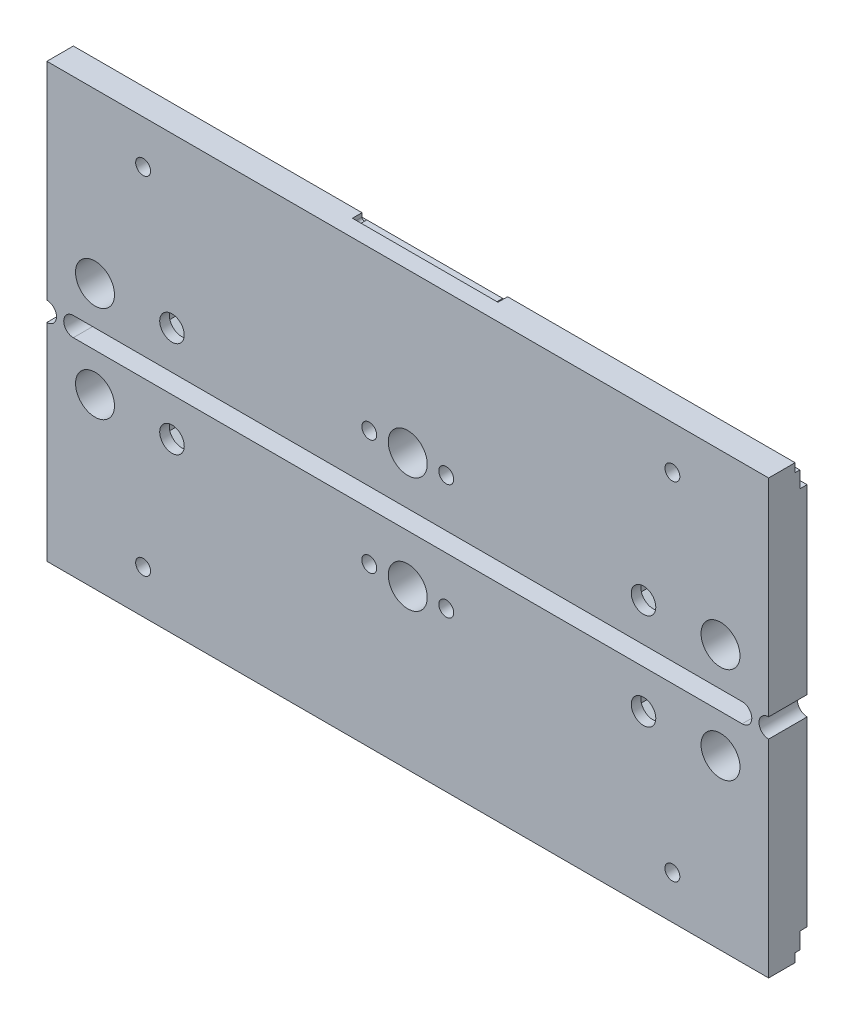
SolidWorks part; units mm, degrees
ref_plane "前视基准面" through (0, 0, 0) normal (0, 0, 1) x (1, 0, 0)
ref_plane "上视基准面" through (0, 0, 0) normal (0, 1, 0) x (1, 0, 0)
ref_plane "右视基准面" through (0, 0, 0) normal (1, 0, 0) x (0, 0, -1)
sketch "前视图草图" plane through (0, 0, 0) normal (0, 0, 1) x (1, 0, 0)
  line L0 (0, 0) -> (8.5179, 0) construction
  line L1 (0, 0) -> (0, 5.4227) construction
sketch "草图2" plane through (0, 0, 0) normal (0, 0, 1) x (1, 0, 0)
  line L0 (0, 0) -> (150, 0)
  line L1 (-200000, 0) -> (200008.5179, 0) construction
  line L2 (150, 0) -> (150, 43)
  line L3 (150, 43) -> (0, 43)
  line L4 (0, -200000) -> (0, 200005.4227) construction
  line L5 (0, 43) -> (0, 0)
  line L6 (75, 43) -> (75, 0) construction
  circle A0 centre (10, 8) radius 4.05
  circle A1 centre (75, 10) radius 4.05
  circle A2 centre (140, 8) radius 4.05
  dimension "D3" = 8
  dimension "D5" = 10
  dimension "D9" = 8.1
  dimension "D10" = 8.1
  dimension "D11" = 8.1
  dimension "D1" = 43
  dimension "D2" = 150
  dimension "D4" = 65
  dimension "D6" = 65
  dimension "D7" = 8
extrude "凸台-拉伸1" add sketch "草图2" along normal blind 8
sketch "草图3" plane through (0, 0, 8) normal (0, 0, 1) x (1, 0, 0)
  line L0 (19.088, 8) -> (34.4805, 8) construction
  line L1 (10, 8) -> (10, 16.8386) construction
  line L2 (140, 8) -> (140, 16.5917) construction
  circle A0 centre (10, 8) radius 4.05 construction
  circle A2 centre (26, 8) radius 2.55
  circle A3 centre (124, 8) radius 2.55
  circle A4 centre (10, 8) radius 4.05 construction
  point P9 (0, 0)
  dimension "D4" = 5.1
  dimension "D5" = 5.1
  dimension "D2" = 16
  dimension "D3" = 16
extrude "切除-拉伸1" cut sketch "草图3" against normal through all
sketch "草图28" plane through (0, 0, 0) normal (0, 0, -1) x (-1, 0, 0)
  line L0 (-150, 0) -> (-150, 43) construction
  line L1 (-119.9, 5.6329) -> (-119.9, 10.3671)
  line L2 (-119.9, 10.3671) -> (-124, 12.7343)
  line L3 (-124, 12.7343) -> (-128.1, 10.3671)
  line L4 (-128.1, 10.3671) -> (-128.1, 5.6329)
  line L5 (-128.1, 5.6329) -> (-124, 3.2657)
  line L6 (-124, 3.2657) -> (-119.9, 5.6329)
  line L7 (-21.9, 5.6329) -> (-21.9, 10.3671)
  line L8 (-21.9, 10.3671) -> (-26, 12.7343)
  line L9 (-26, 12.7343) -> (-30.1, 10.3671)
  line L10 (-30.1, 10.3671) -> (-30.1, 5.6329)
  line L11 (-30.1, 5.6329) -> (-26, 3.2657)
  line L12 (-26, 3.2657) -> (-21.9, 5.6329)
  circle A0 centre (-124, 8) radius 4.1 construction
  circle A1 centre (-26, 8) radius 4.1 construction
  dimension "D1" = 8.2
extrude "切除-拉伸16" cut sketch "草图28" against normal blind 6
sketch "草图4" plane through (150, 0, 0) normal (1, 0, 0) x (0, 0, -1)
  line L1 (0, -200000) -> (0, 200005.4227) construction
  line L2 (-1.5, 41.2) -> (-2.5, 41.2)
  line L3 (-2.5, 41.2) -> (-2.5, 43)
  line L4 (-8, 43) -> (0, 43) construction
  line L5 (-2.5, 43) -> (0, 43)
  line L6 (-1.5, 41.2) -> (-1.5, 37.8)
  line L7 (-1.5, 37.8) -> (0, 37.8)
  line L8 (0, 37.8) -> (0, 43)
  dimension "D1" = 3.4
  dimension "D2" = 2.5
  dimension "D3" = 1.5
  dimension "D4" = 1.8
extrude "切除-拉伸2" cut sketch "草图4" against normal through all
sketch "草图5" plane through (0, 0, 8) normal (0, 0, 1) x (1, 0, 0)
  line L0 (75, 10) -> (91.5376, 10) construction
  circle A0 centre (75, 10) radius 8 construction
  circle A1 centre (83, 10) radius 1.55
  circle A2 centre (67, 10) radius 1.55
  dimension "D1" = 3.1
  dimension "D2" = 3.1
  dimension "D3" = 16
extrude "切除-拉伸3" cut sketch "草图5" against normal through all
sketch "草图7" plane through (0, 0, 0) normal (0, 0, -1) x (-1, 0, 0)
  line L0 (-40, 12) -> (-40, -8.3696) construction
  line L1 (-26, 10) -> (-26, -2.3368) construction
  line L2 (200000, 0) -> (-200008.5179, 0) construction
  line L6 (-30.05, 10) -> (-30.05, 2.5)
  line L7 (-32.55, 0) -> (-19.45, 0)
  line L8 (-21.95, 2.5) -> (-21.95, 10)
  line L9 (-26, 8) -> (-26, 15.9045) construction
  line L13 (0, -200000) -> (0, 200005.4227) construction
  line L14 (-54, 8) -> (-54, 15.9045) construction
  line L15 (-54, 10) -> (-54, -2.3368) construction
  line L16 (-58.05, 2.5) -> (-58.05, 10)
  line L17 (-47.45, 0) -> (-60.55, 0)
  line L18 (-49.95, 10) -> (-49.95, 2.5)
  arc A1 (-21.95, 10) -> (-30.05, 10) centre (-26, 10) ccw
  arc A4 (-32.55, 0) -> (-30.05, 2.5) centre (-32.55, 2.5) ccw
  arc A5 (-21.95, 2.5) -> (-19.45, 0) centre (-19.45, 2.5) ccw
  arc A7 (-58.05, 2.5) -> (-60.55, 0) centre (-60.55, 2.5) cw
  arc A8 (-47.45, 0) -> (-49.95, 2.5) centre (-47.45, 2.5) cw
  arc A9 (-58.05, 10) -> (-49.95, 10) centre (-54, 10) cw
  dimension "D1" = 40
  dimension "D4" = 8.1
  dimension "D7" = 2.5
  dimension "D8" = 2.5
  dimension "D3" = 10
extrude "切除-拉伸4" [suppressed] cut sketch "草图7" against normal blind 6
sketch "草图8" plane through (0, 0, 0) normal (0, 0, -1) x (-1, 0, 0)
  line L0 (-75, 10) -> (-92.3165, 10) construction
  line L1 (-75, 20) -> (-75, 35.6562) construction
  line L2 (-65.5, 12.85) -> (-84.5, 12.85)
  line L3 (-84.5, 7.15) -> (-65.5, 7.15)
  line L4 (200000, 0) -> (-200008.5179, 0) construction
  line L5 (-150, 0) -> (-150, 37.8) construction
  line L6 (-80.15, 8.3546) -> (-80.15, 11.6454)
  line L7 (-80.15, 11.6454) -> (-83, 13.2909)
  line L8 (-83, 13.2909) -> (-85.85, 11.6454)
  line L9 (-85.85, 11.6454) -> (-85.85, 8.3546)
  line L10 (-85.85, 8.3546) -> (-83, 6.7091)
  line L11 (-83, 6.7091) -> (-80.15, 8.3546)
  line L12 (-64.15, 8.3546) -> (-64.15, 11.6454)
  line L13 (-64.15, 11.6454) -> (-67, 13.2909)
  line L14 (-67, 13.2909) -> (-69.85, 11.6454)
  line L15 (-69.85, 11.6454) -> (-69.85, 8.3546)
  line L16 (-69.85, 8.3546) -> (-67, 6.7091)
  line L17 (-67, 6.7091) -> (-64.15, 8.3546)
  arc A0 (-65.5, 7.15) -> (-65.5, 12.85) centre (-65.5, 10) ccw
  arc A1 (-84.5, 12.85) -> (-84.5, 7.15) centre (-84.5, 10) ccw
  circle A2 centre (-83, 10) radius 2.85 construction
  circle A3 centre (-67, 10) radius 2.85 construction
  circle A4 centre (-75, 10) radius 4.05 construction
  circle A5 centre (-75, 10) radius 4.05 construction
  dimension "D1" = 5.7
  dimension "D2" = 9.5
  dimension "D3" = 9.5
  dimension "D4" = 10
  dimension "D5" = 5.7
extrude "切除-拉伸5" cut sketch "草图8" against normal blind 4.5 contours L9 L10 L11 L6 L7 L8 | L17 L12 L13 L14 L15 L16
sketch "草图20" plane through (0, 0, 0) normal (0, 0, -1) x (-1, 0, 0)
  circle A0 centre (-75, 10) radius 5.5
  dimension "D1" = 11
sketch "草图25" plane through (0, 0, 0) normal (0, 0, -1) x (-1, 0, 0)
  line L0 (-51.4471, 34) -> (-40.1512, 34) construction
  line L1 (-130, 37.1428) -> (-130, 21.9179) construction
  line L2 (-20, 37.1428) -> (-20, 21.9179) construction
  line L3 (0, 43) -> (-150, 43) construction
  circle A0 centre (-130, 34) radius 1.55
  circle A1 centre (-20, 34) radius 1.55
  circle A2 centre (-75, 10) radius 4.05 construction
  circle A3 centre (-75, 10) radius 4.05 construction
  dimension "D4" = 3.1
  dimension "D5" = 3.1
  dimension "D1" = 9
  dimension "D2" = 55
  dimension "D3" = 55
extrude "切除-拉伸13" cut sketch "草图25" against normal through all
sketch "草图19" plane through (0, 0, 2.5) normal (0, 0, -1) x (-1, 0, 0)
  line L0 (0, 43) -> (-150, 43) construction
  line L1 (-60, 43) -> (-90.2479, 43)
  line L2 (-60, 43) -> (-60, 42.2)
  line L3 (-61, 42.2) -> (-89.2479, 42.2)
  line L4 (-90.2479, 43) -> (-90.2479, 42.2)
  line L6 (-90.2479, 81.6491) -> (-90.2479, -28.0472) construction
  line L7 (0, 41.2) -> (-150, 41.2) construction
  line L8 (-56.3335, 41.7) -> (-52.9089, 41.7) construction
  line L9 (-90.2479, 1028.5823) -> (-90.2479, 42.2) construction
  line L10 (-60, 1028.5823) -> (-60, 41.7) construction
  line L11 (-90.2479, 41.7) -> (-90.2479, -973.3) construction
  line L12 (-60, 41.7) -> (-60, -973.3) construction
  arc A3 (-90.2479, 42.2) -> (-89.2479, 42.2) centre (-89.7479, 42.2) ccw
  arc A6 (-61, 42.2) -> (-60, 42.2) centre (-60.5, 42.2) ccw
  dimension "D3" = 1
  dimension "D4" = 1
  dimension "D5" = 30.2479
  dimension "D6" = 15
  dimension "D2" = 0.8
  dimension "D1" = 0.5
extrude "切除-拉伸11" cut sketch "草图19" against normal blind 2
sketch "草图22" plane through (0, 0, 8) normal (0, 0, 1) x (1, 0, 0)
  line L1 (0, -200000) -> (0, 200005.4227) construction
  line L2 (0, -4) -> (5.5, -4)
  line L4 (150, 0) -> (144.5, 0)
  line L5 (3.5, 1.9875) -> (3.5, -4.1402) construction
  line L6 (146.5, -11.5647) -> (146.5, -5.1636) construction
  line L7 (150, 0) -> (150, 43) construction
  line L8 (144.5, -4) -> (150, -4)
  line L9 (5.5, 0) -> (0, 0)
  line L10 (148, -2.9635) -> (148, -4.3032) construction
  line L11 (2, -8.393) -> (2, -15.1693) construction
  arc A0 (5.5, 0) -> (5.5, -4) centre (5.5, -2) ccw
  arc A1 (144.5, -4) -> (144.5, 0) centre (144.5, -2) ccw
  arc A2 (0, -4) -> (0, 0) centre (0, -2) ccw
  arc A3 (150, 0) -> (150, -4) centre (150, -2) ccw
  dimension "D1" = 3.5
  dimension "D2" = 3.5
  dimension "D3" = 4
  dimension "D4" = 2
  dimension "D5" = 2
extrude "凸台-拉伸2" add sketch "草图22" against normal blind 8
ref_plane "基准面1" through (0, -2, 0) normal (0, -1, 0) x (-1, 0, 0)
mirror "镜向2" about plane through (0, -2, 0) normal (0, -1, 0) of "切除-拉伸16", "切除-拉伸1", "切除-拉伸13", "切除-拉伸11", "切除-拉伸5", "切除-拉伸2", "凸台-拉伸1", "切除-拉伸3"
sketch "草图23" plane through (0, 0, 0) normal (0, 0, -1) x (-1, 0, 0)
  line L0 (-80, 0) -> (0, 0)
  line L1 (0, 0) -> (0, -4)
  line L2 (0, -4) -> (-80, -4)
  line L3 (-80, -4) -> (-80, 0)
sketch "草图26" plane through (0, 0, 0) normal (0, 0, -1) x (-1, 0, 0)
  circle A0 centre (-140, -12) radius 6.025
  circle A1 centre (-10, -12) radius 6.025
  dimension "D1" = 12.05
  dimension "D2" = 12.05
extrude "切除-拉伸14" [suppressed] cut sketch "草图26" against normal through all
sketch "草图27" plane through (0, 0, 0) normal (0, 0, -1) x (-1, 0, 0)
  line L0 (-136, 37.8) -> (-136, -41.8) construction
  line L3 (-150, 12) -> (0, 12) construction
  line L4 (-150, 0) -> (-150, 37.8) construction
  line L5 (0, -200000) -> (0, 200005.4227) construction
  line L6 (-75, 37.8) -> (-75, -41.8) construction
  line L7 (0, 37.8) -> (-150, 37.8) construction
  line L8 (0, -41.8) -> (-150, -41.8) construction
  line L9 (0, 37.8) -> (-150, 37.8) construction
  line L10 (0, -41.8) -> (-150, -41.8) construction
  line L11 (-150, -16) -> (0, -16) construction
  line L12 (-150, -4) -> (-150, -41.8) construction
  line L13 (200000, 0) -> (-200008.5179, 0) construction
  line L14 (0, -4) -> (-80, -4) construction
  circle A0 centre (-136, 12) radius 3
  circle A1 centre (-136, -16) radius 1.55
  circle A2 centre (-14, -16) radius 1.55
  circle A3 centre (-14, 12) radius 3
  dimension "D4" = 3.1
  dimension "D5" = 6
  dimension "D1" = 12
  dimension "D2" = 12
  dimension "D3" = 14
extrude "切除-拉伸15" [suppressed] cut sketch "草图27" against normal through all
sketch "草图24" plane through (0, 0, 8) normal (0, 0, 1) x (1, 0, 0)
  line L0 (80, -4) -> (80, 0)
  line L1 (80, 0) -> (0, 0)
  line L2 (0, 0) -> (0, -4)
  line L3 (0, -4) -> (80, -4)
sketch "草图29" plane through (0, 0, 0) normal (0, 0, -1) x (-1, 0, 0)
  circle A0 centre (-75, -14) radius 5.5
  dimension "D1" = 11
extrude "切除-拉伸17" [suppressed] cut sketch "草图29" against normal through all
